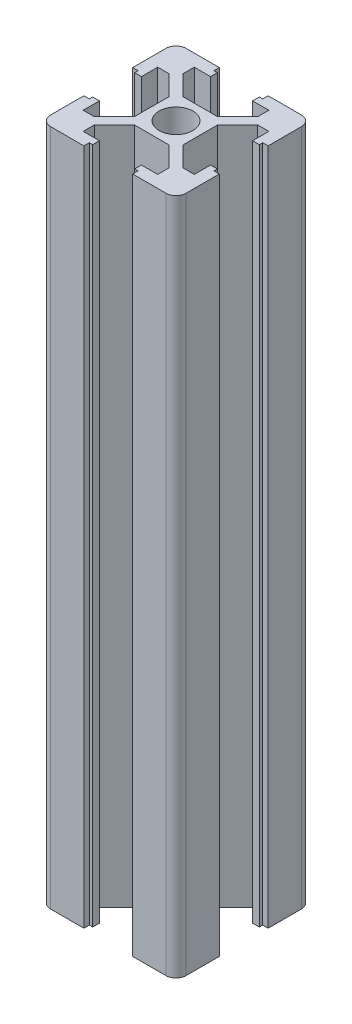
SolidWorks part; units mm, degrees
ref_plane "前视基准面" through (0, 0, 0) normal (0, 0, 1) x (1, 0, 0)
ref_plane "上视基准面" through (0, 0, 0) normal (0, 1, 0) x (1, 0, 0)
ref_plane "右视基准面" through (0, 0, 0) normal (1, 0, 0) x (0, 0, -1)
other "Configuration Table"
sketch "草图1" plane through (0, 0, 0) normal (0, 1, 0) x (1, 0, 0)
  line L0 (-0.9137, 0.6908) -> (-0.9137, 3.7908) construction
  line L1 (-0.9137, 3.2301) -> (-0.9137, -1.8486)
  line L2 (5.2257, 4.2908) -> (0.147, 4.2908)
  line L3 (6.2863, -1.8486) -> (6.2863, 3.2301)
  line L4 (0.147, -2.9092) -> (5.2257, -2.9092)
  line L5 (-7.3137, 0.6908) -> (12.6863, 0.6908) construction
  line L6 (2.6863, 10.6908) -> (2.6863, -9.3092) construction
  line L7 (-7.3137, 10.6908) -> (2.6863, 0.6908) construction
  line L8 (-7.3137, 4.2908) -> (-0.9137, 4.2908) construction
  line L9 (-6.5137, 3.7908) -> (-0.4137, 3.7908) construction
  line L10 (-5.5137, 6.1908) -> (-2.8137, 6.1908) construction
  line L11 (-3.8743, 6.1908) -> (-0.9137, 3.2301) construction
  line L12 (-7.3137, 9.1908) -> (-7.3137, 4.2908)
  line L13 (-7.3137, 4.2908) -> (-6.5137, 4.2908)
  line L14 (-6.5137, 4.2908) -> (-6.5137, 3.7908)
  line L15 (-6.5137, 3.7908) -> (-5.5137, 3.7908)
  line L16 (-5.5137, 3.7908) -> (-5.5137, 6.1908)
  line L17 (-5.5137, 6.1908) -> (-3.8743, 6.1908)
  line L18 (-3.8743, 6.1908) -> (-0.9137, 3.2301)
  line L19 (-0.4137, 9.8908) -> (-0.4137, 8.8908)
  line L20 (-0.9137, 9.8908) -> (-0.4137, 9.8908)
  line L21 (-0.9137, 10.6908) -> (-0.9137, 9.8908)
  line L22 (-5.8137, 10.6908) -> (-0.9137, 10.6908)
  line L23 (-0.4137, 8.8908) -> (-2.8137, 8.8908)
  line L24 (-2.8137, 8.8908) -> (-2.8137, 7.2514)
  line L25 (-2.8137, 7.2514) -> (0.147, 4.2908)
  line L26 (12.6863, 10.6908) -> (2.6863, 0.6908) construction
  line L27 (8.1863, 7.2514) -> (5.2257, 4.2908)
  line L28 (8.1863, 8.8908) -> (8.1863, 7.2514)
  line L29 (5.7863, 8.8908) -> (8.1863, 8.8908)
  line L30 (5.7863, 9.8908) -> (5.7863, 8.8908)
  line L31 (6.2863, 9.8908) -> (5.7863, 9.8908)
  line L32 (6.2863, 10.6908) -> (6.2863, 9.8908)
  line L33 (11.1863, 10.6908) -> (6.2863, 10.6908)
  line L34 (12.6863, 9.1908) -> (12.6863, 4.2908)
  line L35 (12.6863, 4.2908) -> (11.8863, 4.2908)
  line L36 (11.8863, 4.2908) -> (11.8863, 3.7908)
  line L37 (11.8863, 3.7908) -> (10.8863, 3.7908)
  line L38 (10.8863, 3.7908) -> (10.8863, 6.1908)
  line L39 (10.8863, 6.1908) -> (9.247, 6.1908)
  line L40 (9.247, 6.1908) -> (6.2863, 3.2301)
  line L41 (12.6863, -9.3092) -> (2.6863, 0.6908) construction
  line L42 (9.247, -4.8092) -> (6.2863, -1.8486)
  line L43 (10.8863, -4.8092) -> (9.247, -4.8092)
  line L44 (10.8863, -2.4092) -> (10.8863, -4.8092)
  line L45 (11.8863, -2.4092) -> (10.8863, -2.4092)
  line L46 (11.8863, -2.9092) -> (11.8863, -2.4092)
  line L47 (12.6863, -2.9092) -> (11.8863, -2.9092)
  line L48 (12.6863, -7.8092) -> (12.6863, -2.9092)
  line L49 (11.1863, -9.3092) -> (6.2863, -9.3092)
  line L50 (6.2863, -9.3092) -> (6.2863, -8.5092)
  line L51 (6.2863, -8.5092) -> (5.7863, -8.5092)
  line L52 (5.7863, -8.5092) -> (5.7863, -7.5092)
  line L53 (5.7863, -7.5092) -> (8.1863, -7.5092)
  line L54 (8.1863, -7.5092) -> (8.1863, -5.8699)
  line L55 (8.1863, -5.8699) -> (5.2257, -2.9092)
  line L56 (-7.3137, -9.3092) -> (2.6863, 0.6908) construction
  line L57 (-2.8137, -5.8699) -> (0.147, -2.9092)
  line L58 (-2.8137, -7.5092) -> (-2.8137, -5.8699)
  line L59 (-0.4137, -7.5092) -> (-2.8137, -7.5092)
  line L60 (-0.4137, -8.5092) -> (-0.4137, -7.5092)
  line L61 (-0.9137, -8.5092) -> (-0.4137, -8.5092)
  line L62 (-0.9137, -9.3092) -> (-0.9137, -8.5092)
  line L63 (-5.8137, -9.3092) -> (-0.9137, -9.3092)
  line L64 (-7.3137, -7.8092) -> (-7.3137, -2.9092)
  line L65 (-7.3137, -2.9092) -> (-6.5137, -2.9092)
  line L66 (-6.5137, -2.9092) -> (-6.5137, -2.4092)
  line L67 (-6.5137, -2.4092) -> (-5.5137, -2.4092)
  line L68 (-5.5137, -2.4092) -> (-5.5137, -4.8092)
  line L69 (-5.5137, -4.8092) -> (-3.8743, -4.8092)
  line L70 (-3.8743, -4.8092) -> (-0.9137, -1.8486)
  arc A0 (-7.3137, 9.1908) -> (-5.8137, 10.6908) centre (-5.8137, 9.1908) cw
  circle A1 centre (2.6863, 0.6908) radius 2.5
  arc A2 (11.1863, 10.6908) -> (12.6863, 9.1908) centre (11.1863, 9.1908) cw
  arc A3 (12.6863, -7.8092) -> (11.1863, -9.3092) centre (11.1863, -7.8092) cw
  arc A4 (-5.8137, -9.3092) -> (-7.3137, -7.8092) centre (-5.8137, -7.8092) cw
  point P13 (2.6863, 0.6908)
  point P84 (2.6863, 0.6908)
  dimension "D8" = 1.5
  dimension "D9" = 5
  dimension "D1" = 20
  dimension "D2" = 6.2
  dimension "D3" = 7.2
  dimension "D4" = 11
  dimension "D5" = 1.5
  dimension "D6" = 0.8
  dimension "D7" = 1.8
  dimension "D10" = 7.2
extrude "凸台-拉伸1" add sketch "草图1" along normal blind 100
